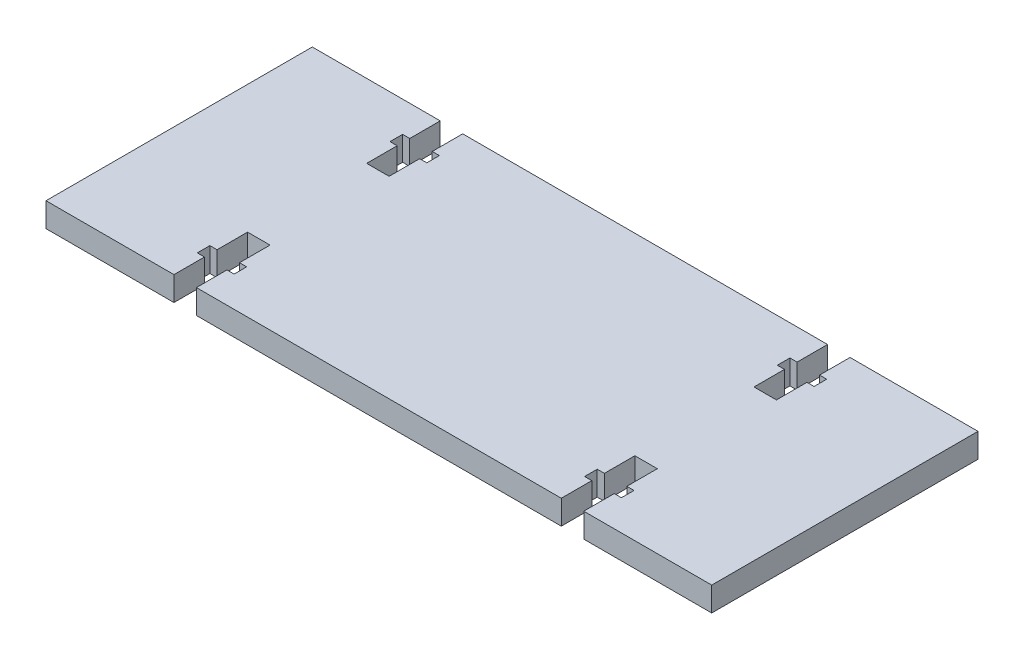
SolidWorks part; units mm, degrees
ref_plane "Front Plane" through (0, 0, 0) normal (0, 0, 1) x (1, 0, 0)
ref_plane "Top Plane" through (0, 0, 0) normal (0, 1, 0) x (1, 0, 0)
ref_plane "Right Plane" through (0, 0, 0) normal (1, 0, 0) x (0, 0, -1)
sketch "Sketch1" plane through (0, 0, 0) normal (0, 1, 0) x (1, 0, 0)
  line L1 (-43.6562, -17.4625) -> (43.6563, -17.4625)
  line L2 (-43.6562, -17.4625) -> (-43.6562, 17.4625)
  line L3 (-43.6562, 17.4625) -> (43.6563, 17.4625)
  line L4 (43.6563, -17.4625) -> (43.6563, 17.4625)
  line L5 (-43.6562, -17.4625) -> (43.6563, 17.4625) construction
  line L6 (-43.6562, 17.4625) -> (43.6563, -17.4625) construction
  point P0 (0, 0)
  dimension "D1" = 87.3125
  dimension "D2" = 34.925
extrude "Boss-Extrude1" add sketch "Sketch1" along normal blind 3.175
sketch "Sketch3" plane through (0, 0, 0) normal (0, -1, 0) x (1, 0, 0)
  line L0 (-43.6562, 17.4625) -> (43.6563, 17.4625) construction
  line L1 (-26.8732, 17.4625) -> (-23.9268, 17.4625)
  line L2 (-26.8732, 17.4625) -> (-26.8732, 13.462)
  line L3 (-26.8732, 7.8105) -> (-23.9268, 7.8105)
  line L4 (-23.9268, 17.4625) -> (-23.9268, 13.462)
  line L5 (-26.8732, 17.4625) -> (-23.9268, 7.8105) construction
  line L6 (-26.8732, 13.462) -> (-27.813, 13.462)
  line L7 (-22.987, 11.811) -> (-23.9268, 11.811)
  line L8 (-22.987, 11.811) -> (-22.987, 13.462)
  line L9 (-22.987, 13.462) -> (-23.9268, 13.462)
  line L10 (-27.813, 11.811) -> (-27.813, 13.462)
  line L11 (-22.987, 11.811) -> (-27.813, 13.462) construction
  line L12 (-22.987, 13.462) -> (-27.813, 11.811) construction
  line L13 (-23.9268, 11.811) -> (-23.9268, 7.8105)
  line L14 (-26.8732, 11.811) -> (-27.813, 11.811)
  line L15 (-26.8732, 11.811) -> (-26.8732, 7.8105)
  line L16 (-25.4, 7.8105) -> (-25.4, 17.4625) construction
  line L17 (0, 17.4625) -> (0, -17.4625) construction
  line L18 (43.6563, -17.4625) -> (-43.6562, -17.4625) construction
  line L19 (25.4, 7.8105) -> (25.4, 17.4625) construction
  line L20 (22.987, 13.462) -> (27.813, 11.811) construction
  line L21 (22.987, 11.811) -> (27.813, 13.462) construction
  line L22 (26.8732, 17.4625) -> (23.9268, 7.8105) construction
  line L23 (26.8732, 11.811) -> (26.8732, 7.8105)
  line L24 (26.8732, 11.811) -> (27.813, 11.811)
  line L25 (23.9268, 11.811) -> (23.9268, 7.8105)
  line L26 (27.813, 11.811) -> (27.813, 13.462)
  line L27 (22.987, 13.462) -> (23.9268, 13.462)
  line L28 (22.987, 11.811) -> (22.987, 13.462)
  line L29 (22.987, 11.811) -> (23.9268, 11.811)
  line L30 (26.8732, 13.462) -> (27.813, 13.462)
  line L31 (23.9268, 17.4625) -> (23.9268, 13.462)
  line L32 (26.8732, 7.8105) -> (23.9268, 7.8105)
  line L33 (26.8732, 17.4625) -> (26.8732, 13.462)
  line L34 (26.8732, 17.4625) -> (23.9268, 17.4625)
  line L35 (-43.6562, 0) -> (-37.7203, 0) construction
  line L36 (-43.6562, -17.4625) -> (-43.6562, 17.4625) construction
  line L37 (26.8732, -17.4625) -> (23.9268, -7.8105) construction
  line L38 (22.987, -11.811) -> (27.813, -13.462) construction
  line L39 (22.987, -13.462) -> (27.813, -11.811) construction
  line L40 (25.4, -7.8105) -> (25.4, -17.4625) construction
  line L41 (26.8732, -17.4625) -> (23.9268, -17.4625)
  line L42 (26.8732, -17.4625) -> (26.8732, -13.462)
  line L43 (26.8732, -7.8105) -> (23.9268, -7.8105)
  line L44 (23.9268, -17.4625) -> (23.9268, -13.462)
  line L45 (26.8732, -13.462) -> (27.813, -13.462)
  line L46 (22.987, -11.811) -> (23.9268, -11.811)
  line L47 (22.987, -11.811) -> (22.987, -13.462)
  line L48 (22.987, -13.462) -> (23.9268, -13.462)
  line L49 (27.813, -11.811) -> (27.813, -13.462)
  line L50 (23.9268, -11.811) -> (23.9268, -7.8105)
  line L51 (26.8732, -11.811) -> (27.813, -11.811)
  line L52 (26.8732, -11.811) -> (26.8732, -7.8105)
  line L53 (-25.4, -7.8105) -> (-25.4, -17.4625) construction
  line L54 (-22.987, -13.462) -> (-27.813, -11.811) construction
  line L55 (-22.987, -11.811) -> (-27.813, -13.462) construction
  line L56 (-26.8732, -17.4625) -> (-23.9268, -7.8105) construction
  line L57 (-26.8732, -11.811) -> (-26.8732, -7.8105)
  line L58 (-26.8732, -11.811) -> (-27.813, -11.811)
  line L59 (-23.9268, -11.811) -> (-23.9268, -7.8105)
  line L60 (-27.813, -11.811) -> (-27.813, -13.462)
  line L61 (-22.987, -13.462) -> (-23.9268, -13.462)
  line L62 (-22.987, -11.811) -> (-22.987, -13.462)
  line L63 (-22.987, -11.811) -> (-23.9268, -11.811)
  line L64 (-26.8732, -13.462) -> (-27.813, -13.462)
  line L65 (-23.9268, -17.4625) -> (-23.9268, -13.462)
  line L66 (-26.8732, -7.8105) -> (-23.9268, -7.8105)
  line L67 (-26.8732, -17.4625) -> (-26.8732, -13.462)
  line L68 (-26.8732, -17.4625) -> (-23.9268, -17.4625)
  point P6 (-25.4, 12.6365)
  point P18 (-25.4, 12.6365)
  point P36 (25.4, 12.6365)
  point P56 (25.4, -12.6365)
  point P71 (-25.4, -12.6365)
  dimension "D1" = 9.652
  dimension "D2" = 2.9464
  dimension "D3" = 1.651
  dimension "D4" = 4.826
  dimension "D5" = 25.4
extrude "Cut-Extrude2" cut sketch "Sketch3" against normal through all
